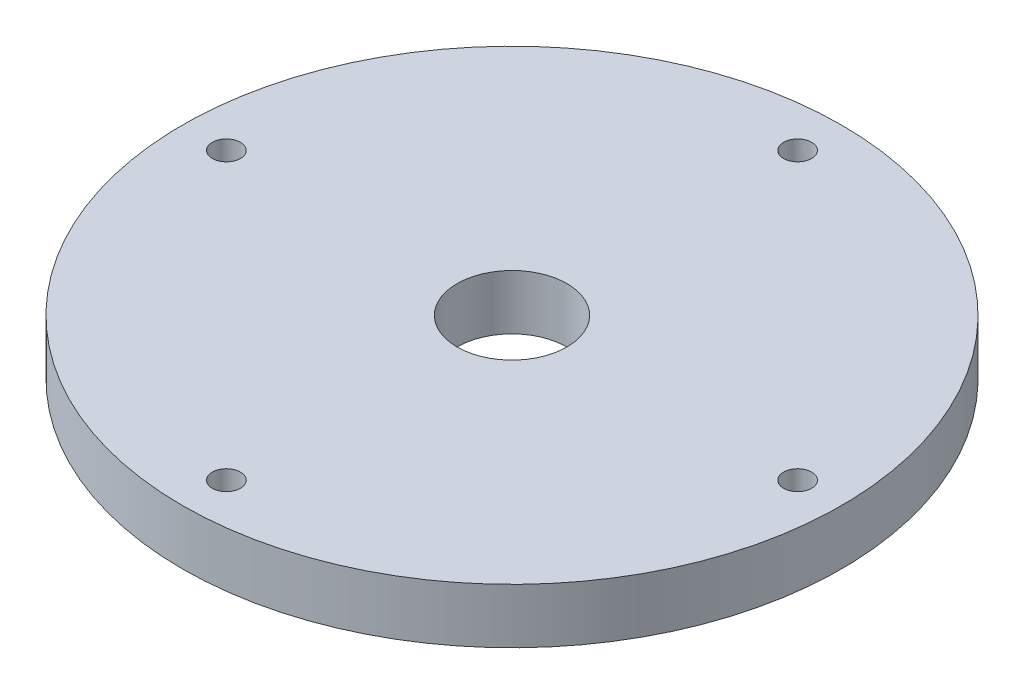
SolidWorks part; units mm, degrees
material "Acrylic (Medium-high impact)"
ref_plane "Front Plane" through (0, 0, 0) normal (0, 0, 1) x (1, 0, 0)
ref_plane "Top Plane" through (0, 0, 0) normal (0, 1, 0) x (1, 0, 0)
ref_plane "Right Plane" through (0, 0, 0) normal (1, 0, 0) x (0, 0, -1)
sketch "Sketch1" plane through (0, 0, 0) normal (0, 1, 0) x (1, 0, 0)
  circle A0 centre (0, 0) radius 38.1
  circle A1 centre (0, 33.02) radius 1.6256
  circle A2 centre (33.02, 0) radius 1.6256
  circle A3 centre (0, -33.02) radius 1.6256
  circle A4 centre (-33.02, 0) radius 1.6256
  circle A5 centre (0, 0) radius 6.35
  circle A6 centre (0, 33.02) radius 1.6256 construction
  point P14 (0, 0)
  dimension "D1" = 76.2
  dimension "D5" = 12.7
  dimension "D4" = 33.02
  dimension "D2" = 4
extrude "Boss-Extrude1" add sketch "Sketch1" along normal blind 6.35
